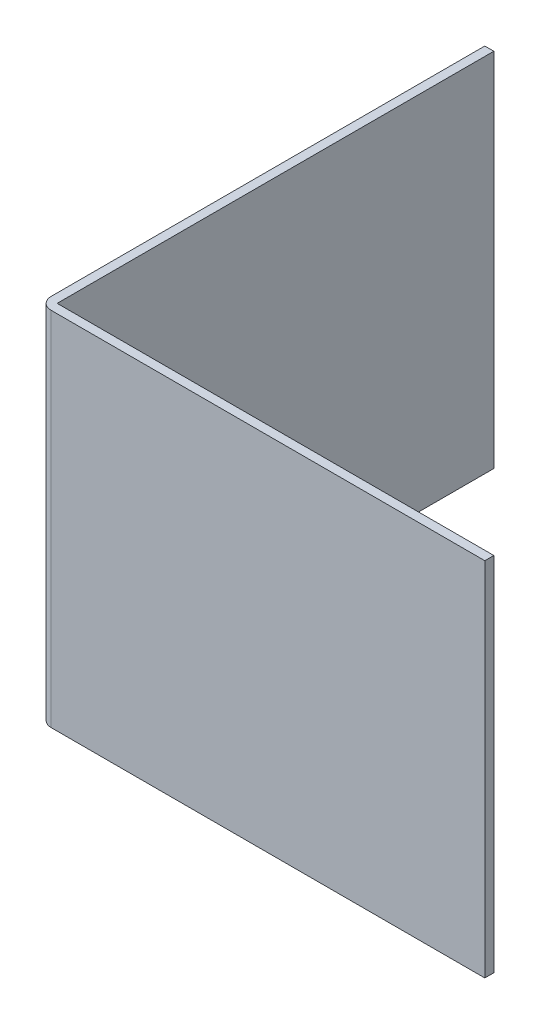
SolidWorks part; units mm, degrees
ref_plane "Front Plane" through (0, 0, 0) normal (0, 0, 1) x (1, 0, 0)
ref_plane "Top Plane" through (0, 0, 0) normal (0, 1, 0) x (1, 0, 0)
ref_plane "Right Plane" through (0, 0, 0) normal (1, 0, 0) x (0, 0, -1)
sketch "Sketch1" plane through (0, 0, 0) normal (0, 1, 0) x (1, 0, 0)
  line L0 (145, 0) -> (0, 0)
  line L1 (0, 0) -> (0, 145)
  line L2 (0, 145) -> (-3, 145)
  line L3 (-3, 145) -> (-3, -3)
  line L4 (-3, -3) -> (145, -3)
  line L5 (145, -3) -> (145, 0)
  dimension "D1" = 145
  dimension "D2" = 145
  dimension "D3" = 3
  dimension "D4" = 3
extrude "Boss-Extrude1" add sketch "Sketch1" along normal blind 120
fillet "Fillet1" radius 4 1 edges at (-3, 60, 3)
